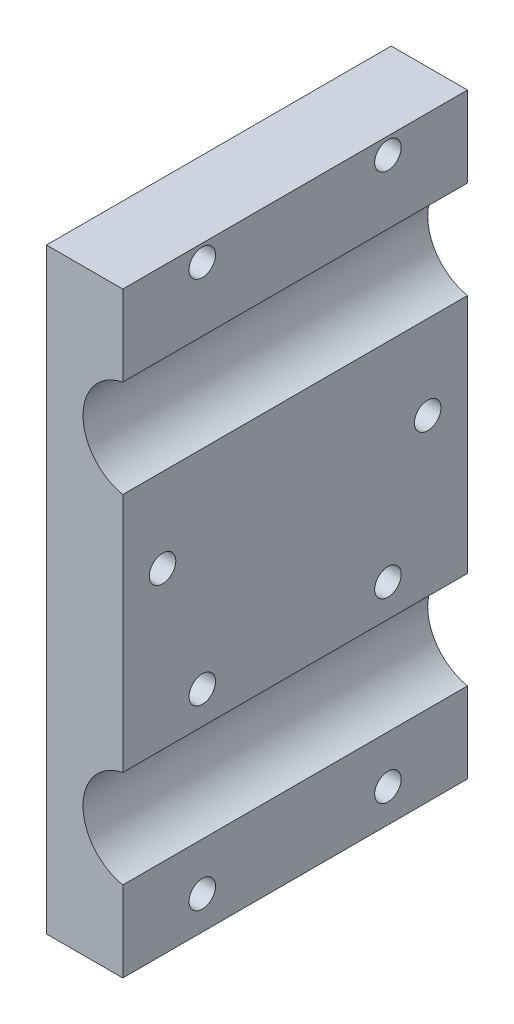
SolidWorks part; units mm, degrees
material "ABS"
ref_plane "Front Plane" through (0, 0, 0) normal (0, 0, 1) x (1, 0, 0)
ref_plane "Top Plane" through (0, 0, 0) normal (0, 1, 0) x (1, 0, 0)
ref_plane "Right Plane" through (0, 0, 0) normal (1, 0, 0) x (0, 0, -1)
sketch "Sketch1" plane through (0, 0, 0) normal (0, 0, 1) x (1, 0, 0)
  line L2 (0, 0) -> (0, -90)
  line L16 (0, 0) -> (-11.5, 0)
  line L17 (-11.5, 0) -> (-11.5, -90)
  line L18 (-11.5, -90) -> (0, -90)
  line L19 (-56.1833, -45) -> (48.7099, -45) construction
  circle A2 centre (1.5, -19.5) radius 7.5
  circle A3 centre (1.5, -70.5) radius 7.5
  point P11 (0, -45)
  dimension "D3" = 11.5
  dimension "D6" = 25.5
  dimension "D2" = 51
  dimension "D4" = 15
  dimension "D5" = 1.5
  dimension "D10" = 90
extrude "Boss-Extrude1" add sketch "Sketch1" along normal blind 52 contours L17 L19 L2 A2 L16 | L19 L17 L18 L2 A3
sketch "Sketch2" plane through (0, 0, 0) normal (1, 0, 0) x (0, 0, -1)
  line L0 (-26, 2.9897) -> (-26, -94.3027) construction
  line L1 (-52, 0) -> (0, 0) construction
  line L2 (-52, 0) -> (-52, -12.1515) construction
  line L3 (-52, -90) -> (0, -90) construction
  line L4 (-52, 0) -> (0, 0) construction
  circle A3 centre (-40, -2.5) radius 2
  circle A4 centre (-40, -85) radius 2
  circle A5 centre (-12, -85) radius 2
  circle A6 centre (-12, -2.5) radius 2
  point P4 (-26, 0)
  dimension "D1" = 12
  dimension "D5" = 4
  dimension "D6" = 5
  dimension "D7" = 2.5
extrude "Cut-Extrude1" cut sketch "Sketch2" against normal through all
sketch "Esquisse1" plane through (0, 0, 0) normal (1, 0, 0) x (0, 0, -1)
  line L0 (0, -26.8485) -> (0, -63.1515) construction
  line L1 (-52, -26.8485) -> (-52, -63.1515) construction
  circle A0 centre (-12, -58.25) radius 2
  circle A1 centre (-40, -58.25) radius 2
  circle A2 centre (-40, -85) radius 2 construction
  circle A3 centre (-12, -85) radius 2 construction
  dimension "D1" = 12
  dimension "D2" = 12
  dimension "D3" = 26.75
extrude "Enlèv. mat.-Extru.1" cut sketch "Esquisse1" against normal through all
sketch "Esquisse2" plane through (0, 0, 0) normal (1, 0, 0) x (0, 0, -1)
  line L0 (0, -26.8485) -> (0, -63.1515) construction
  line L1 (-52, 0) -> (0, 0) construction
  line L2 (-52, -26.8485) -> (-52, -63.1515) construction
  circle A0 centre (-6, -39.5) radius 2
  circle A1 centre (-46, -39.5) radius 2
  dimension "D1" = 4
  dimension "D2" = 6
  dimension "D3" = 39.5
  dimension "D4" = 6
extrude "Enlèv. mat.-Extru.2" cut sketch "Esquisse2" against normal through all
